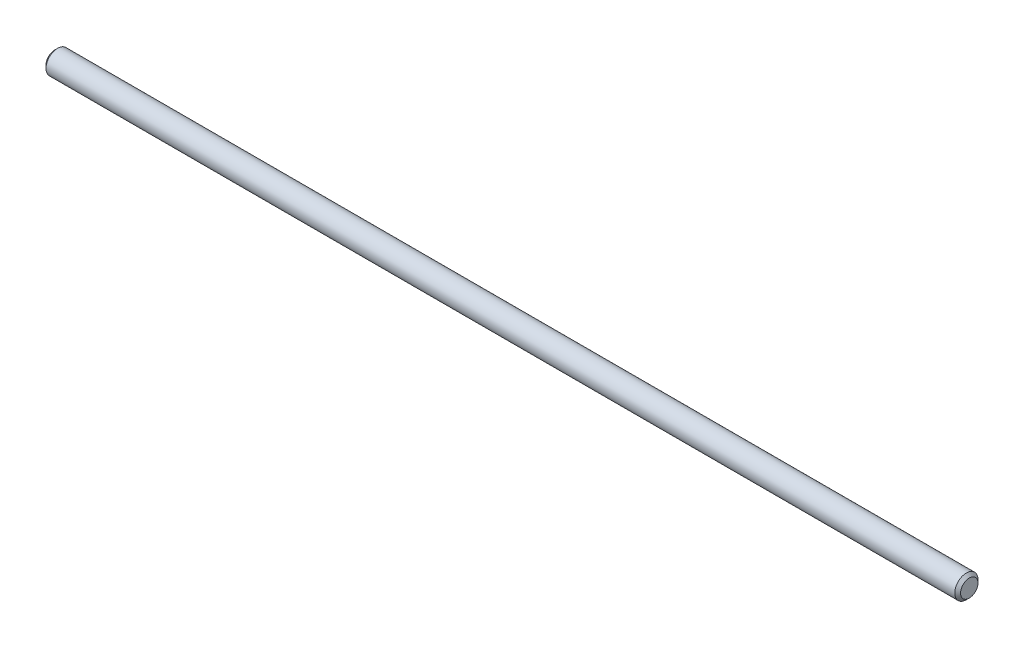
SolidWorks part; units mm, degrees
material "1.4003 (X2CrNi12)"
ref_plane "Front Plane" through (0, 0, 0) normal (0, 0, 1) x (1, 0, 0)
ref_plane "Top Plane" through (0, 0, 0) normal (0, 1, 0) x (1, 0, 0)
ref_plane "Right Plane" through (0, 0, 0) normal (1, 0, 0) x (0, 0, -1)
sketch "Эскиз1" plane through (0, 0, 0) normal (1, 0, 0) x (0, 0, -1)
  circle A0 centre (0, 0) radius 4
  dimension "D1" = 8
extrude "Бобышка-Вытянуть1" add sketch "Эскиз1" along normal blind 315
chamfer "Фаска1" distance 1 angle 45 2 edges at (315, 0, -4) (0, 0, -4)
